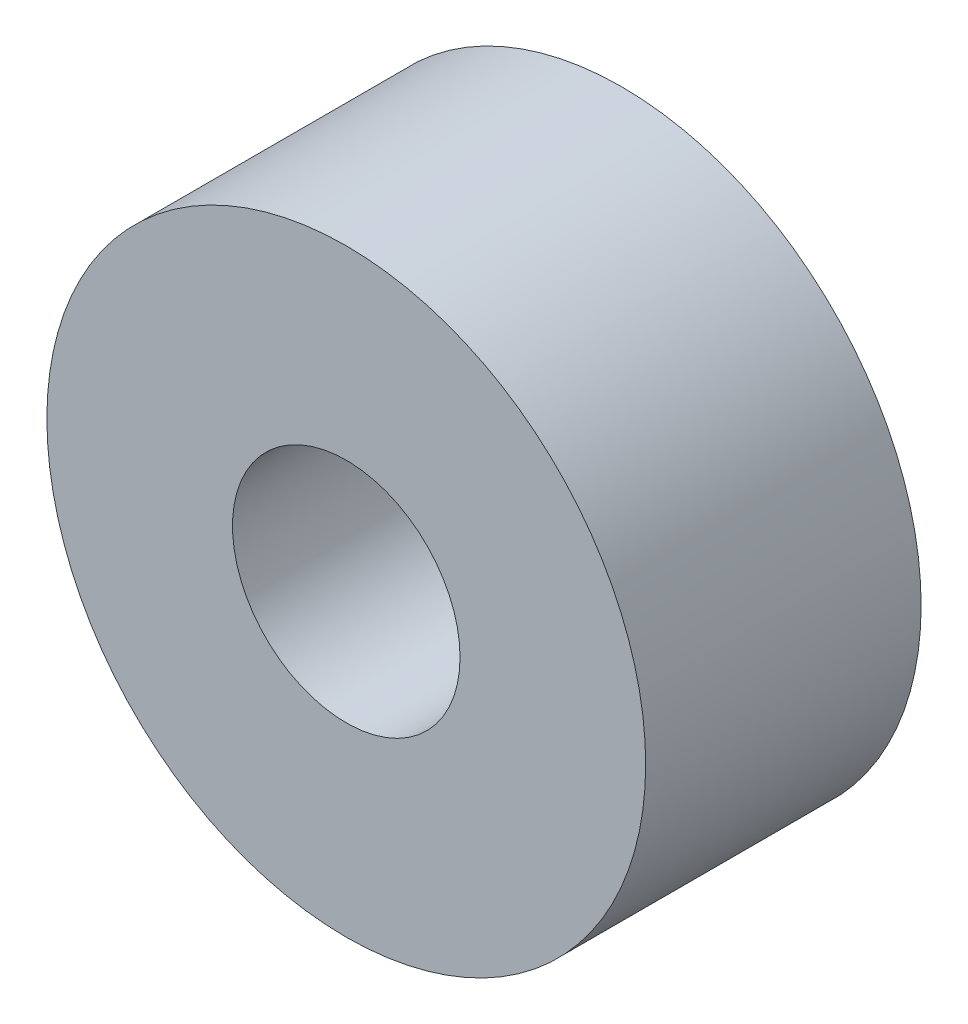
SolidWorks part; units mm, degrees
ref_plane "Front Plane" through (0, 0, 0) normal (0, 0, 1) x (1, 0, 0)
ref_plane "Top Plane" through (0, 0, 0) normal (0, 1, 0) x (1, 0, 0)
ref_plane "Right Plane" through (0, 0, 0) normal (1, 0, 0) x (0, 0, -1)
sketch "Sketch1" plane through (0, 0, 0) normal (0, 0, 1) x (1, 0, 0)
  circle A0 centre (0, 0) radius 2.413
  circle A1 centre (0, 0) radius 6.35
  dimension "D1" = 4.826
  dimension "D2" = 12.7
extrude "Boss-Extrude1" add sketch "Sketch1" along normal blind 5.842
